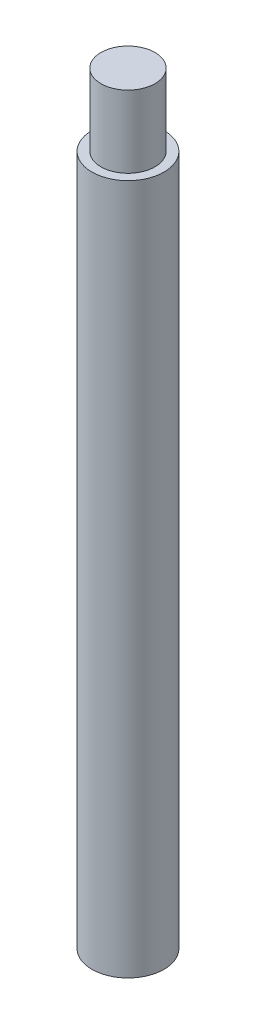
SolidWorks part; units mm, degrees
ref_plane "Front Plane" through (0, 0, 0) normal (0, 0, 1) x (1, 0, 0)
ref_plane "Top Plane" through (0, 0, 0) normal (0, 1, 0) x (1, 0, 0)
ref_plane "Right Plane" through (0, 0, 0) normal (1, 0, 0) x (0, 0, -1)
sketch "Sketch1" plane through (0, 0, 0) normal (0, 1, 0) x (1, 0, 0)
  circle A0 centre (0, 0) radius 3
  point P3 (0, 0)
  dimension "D1" = 6
extrude "Boss-Extrude1" add sketch "Sketch1" along normal blind 57.5
sketch "Sketch2" plane through (0, 57.5, 0) normal (0, 1, 0) x (1, 0, 0)
  circle A0 centre (0, 0) radius 2.25
  dimension "D1" = 4.5
extrude "Boss-Extrude2" add sketch "Sketch2" along normal blind 6
